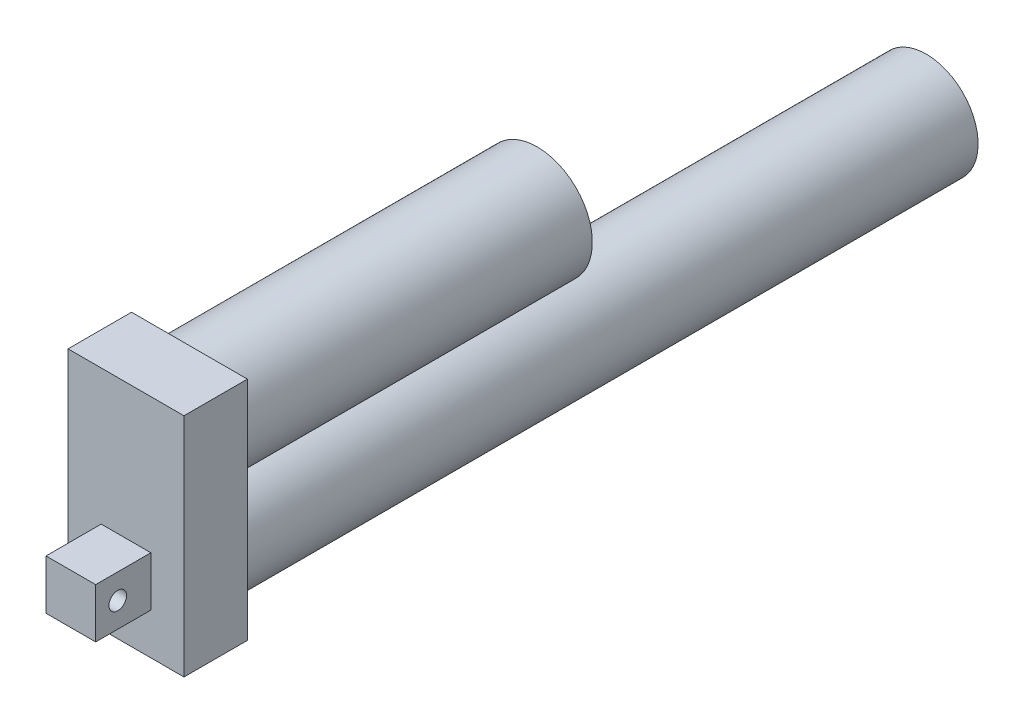
SolidWorks part; units mm, degrees
ref_plane "Front Plane" through (0, 0, 0) normal (0, 0, 1) x (1, 0, 0)
ref_plane "Top Plane" through (0, 0, 0) normal (0, 1, 0) x (1, 0, 0)
ref_plane "Right Plane" through (0, 0, 0) normal (1, 0, 0) x (0, 0, -1)
sketch "Sketch1" plane through (0, 0, 0) normal (0, 0, 1) x (1, 0, 0)
  line L1 (-21, -41) -> (21, -41)
  line L2 (-21, -41) -> (-21, 41)
  line L3 (-21, 41) -> (21, 41)
  line L4 (21, -41) -> (21, 41)
  line L5 (-21, -41) -> (21, 41) construction
  line L6 (-21, 41) -> (21, -41) construction
  point P0 (0, 0)
  point P6 (-21, 41)
  point P7 (0, 0)
  dimension "D1" = 42
  dimension "D2" = 82
extrude "Boss-Extrude1" add sketch "Sketch1" along normal blind 23
sketch "Sketch2" plane through (0, 0, 23) normal (0, 0, 1) x (1, 0, 0)
  line L0 (-21, -41) -> (21, -41) construction
  line L1 (-9, -8) -> (9, -8)
  line L2 (-9, -8) -> (-9, -26)
  line L3 (-9, -26) -> (9, -26)
  line L4 (9, -8) -> (9, -26)
  line L5 (-9, -8) -> (9, -26) construction
  line L6 (-9, -26) -> (9, -8) construction
  line L7 (-21, 41) -> (-21, -41) construction
  point P0 (0, -17)
  point P5 (0, 0)
  dimension "D1" = 18
  dimension "D2" = 18
  dimension "D3" = 24
  dimension "D4" = 21
extrude "Boss-Extrude2" add sketch "Sketch2" along normal blind 20
sketch "Sketch3" plane through (9, 0, 0) normal (1, 0, 0) x (0, 0, -1)
  line L0 (-23, -41) -> (-23, 41) construction
  line L1 (-43, -26) -> (-23, -26) construction
  circle A0 centre (-35, -17) radius 3.2
  point P2 (-78.6237, 2.0859)
  dimension "D1" = 12
  dimension "D2" = 9
extrude "Cut-Extrude1" cut sketch "Sketch3" against normal blind 21
sketch "Sketch4" plane through (0, 0, 0) normal (0, 0, -1) x (-1, 0, 0)
  circle A0 centre (0, -19.779) radius 18.8
  point P2 (0, -19.779)
  dimension "D1" = 37.6
extrude "Boss-Extrude3" add sketch "Sketch4" along normal blind 267
sketch "Sketch5" plane through (0, 0, 0) normal (0, 0, -1) x (-1, 0, 0)
  circle A0 centre (0, 20.4017) radius 20
  dimension "D1" = 40
extrude "Boss-Extrude4" add sketch "Sketch5" along normal blind 126
sketch "Sketch6" plane through (0, 0, -267) normal (0, 0, -1) x (-1, 0, 0)
  circle A0 centre (0, -19.779) radius 10
extrude "Cut-Extrude2" cut sketch "Sketch6" against normal blind 20
sketch "Sketch7" plane through (0, 0, -247) normal (0, 0, -1) x (-1, 0, 0)
  circle A0 centre (0, -19.779) radius 14
extrude "Cut-Extrude5" cut sketch "Sketch7" against normal blind 247
